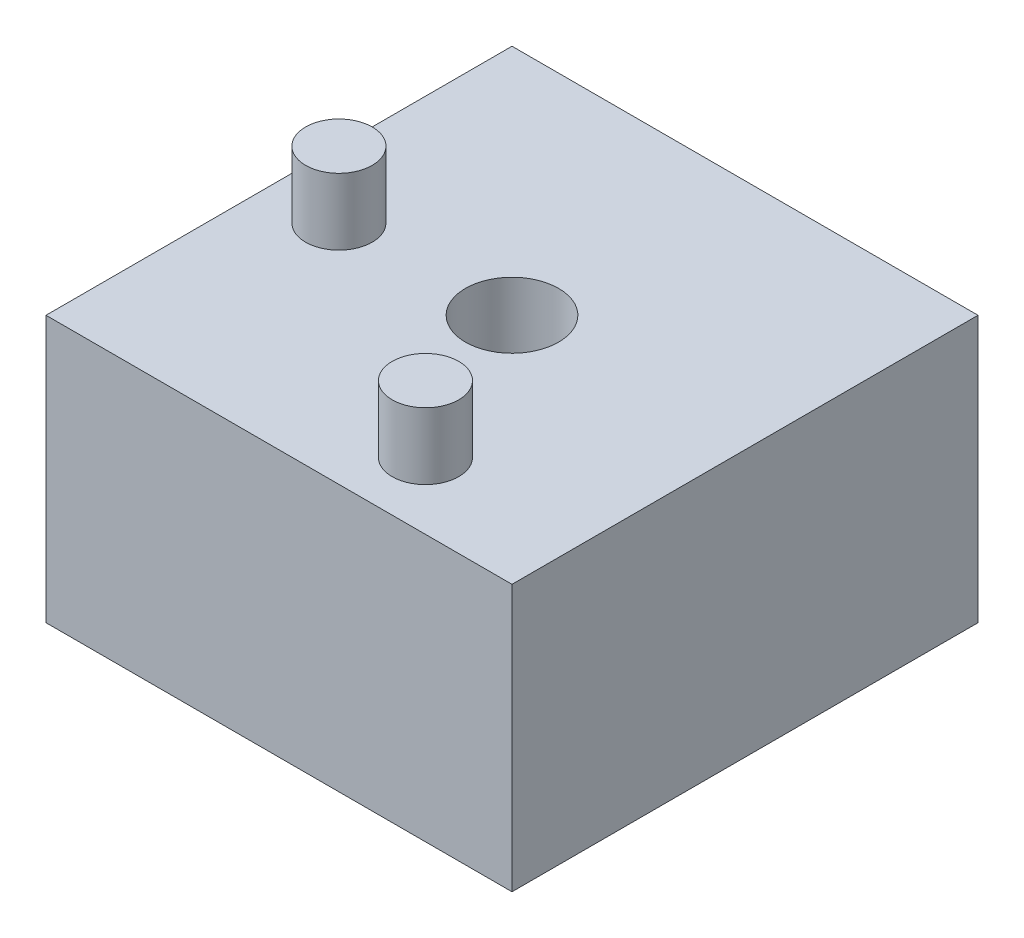
SolidWorks part; units mm, degrees
ref_plane "Front Plane" through (0, 0, 0) normal (0, 0, 1) x (1, 0, 0)
ref_plane "Top Plane" through (0, 0, 0) normal (0, 1, 0) x (1, 0, 0)
ref_plane "Right Plane" through (0, 0, 0) normal (1, 0, 0) x (0, 0, -1)
sketch "Sketch1" plane through (0, 0, 0) normal (0, 1, 0) x (1, 0, 0)
  line L1 (0, 0) -> (44.45, 0)
  line L2 (0, 0) -> (0, 44.45)
  line L3 (0, 44.45) -> (44.45, 44.45)
  line L4 (44.45, 0) -> (44.45, 44.45)
  dimension "D1" = 44.45
  dimension "D2" = 44.45
extrude "Boss-Extrude1" add sketch "Sketch1" along normal blind 25.4
sketch "Sketch2" plane through (0, 25.4, 0) normal (0, 1, 0) x (1, 0, 0)
  line L0 (0, 44.45) -> (44.45, 0) construction
  line L1 (0, 0) -> (44.45, 0) construction
  line L4 (44.45, 44.45) -> (0, 0) construction
  line L11 (44.45, 0) -> (44.45, 44.45) construction
  line L16 (44.45, 44.45) -> (0, 44.45) construction
  line L17 (0, 44.45) -> (0, 0) construction
  circle A1 centre (6.35, 21.59) radius 3.175
  circle A2 centre (29.845, 6.35) radius 3.175
  point P5 (16.0948, 35.56)
  point P6 (17.2772, 35.56)
  dimension "D1" = 6.35
  dimension "D2" = 6.35
  dimension "D3" = 6.35
  dimension "D4" = 6.35
  dimension "D5" = 14.605
  dimension "D6" = 22.86
extrude "Boss-Extrude2" add sketch "Sketch2" along normal blind 6.35
sketch "Sketch3" plane through (0, 25.4, 0) normal (0, 1, 0) x (1, 0, 0)
  line L0 (0, 44.45) -> (44.45, 0) construction
  line L1 (44.45, 44.45) -> (0, 0) construction
  circle A0 centre (22.225, 22.225) radius 2.4257
  dimension "D1" = 4.8514
extrude "Cut-Extrude1" cut sketch "Sketch3" against normal up to surface (25.4 mm away) up to face at (22.225, 0, -22.225)
sketch "Sketch4" plane through (0, 0, 0) normal (0, -1, 0) x (1, 0, 0)
  circle A0 centre (22.225, -22.225) radius 4.445
  dimension "D1" = 8.89
extrude "Cut-Extrude2" cut sketch "Sketch4" against normal blind 25.4
